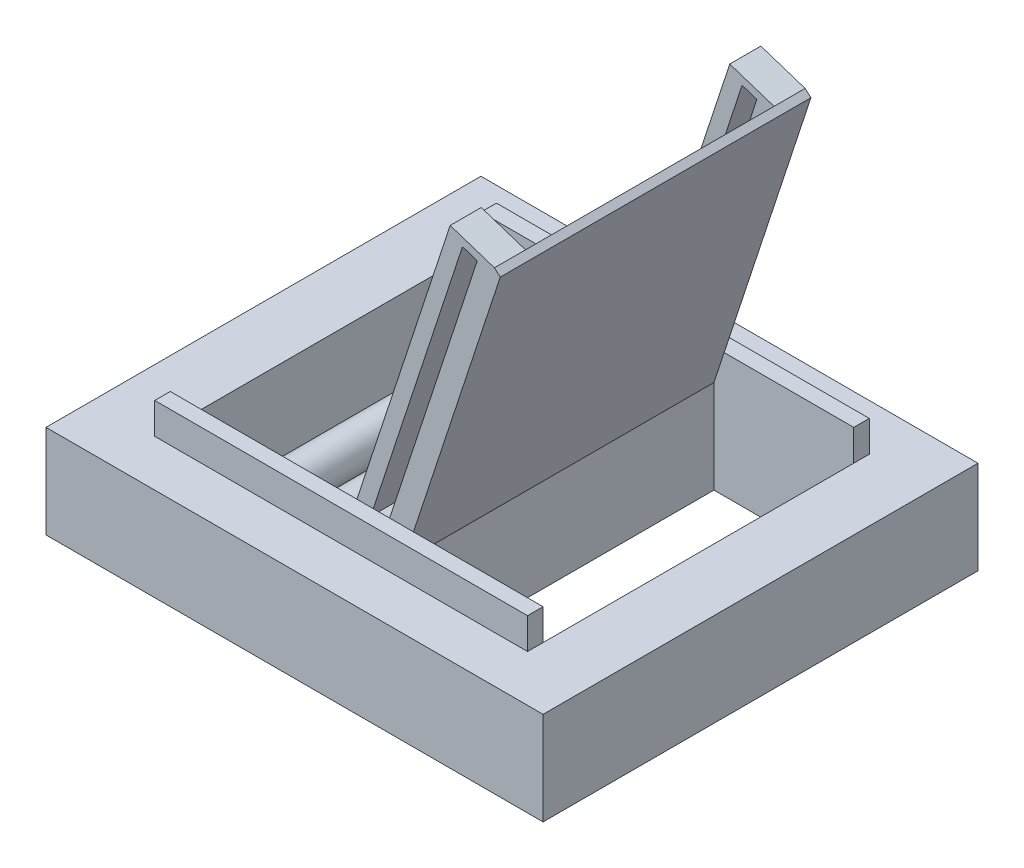
SolidWorks part; units mm, degrees
ref_plane "Front Plane" through (0, 0, 0) normal (0, 0, 1) x (1, 0, 0)
ref_plane "Top Plane" through (0, 0, 0) normal (0, 1, 0) x (1, 0, 0)
ref_plane "Right Plane" through (0, 0, 0) normal (1, 0, 0) x (0, 0, -1)
sketch "Sketch1" plane through (0, 0, 0) normal (0, 1, 0) x (1, 0, 0)
  line L1 (0, 0) -> (812.8, 0)
  line L2 (0, 0) -> (0, -711.2)
  line L3 (0, -711.2) -> (812.8, -711.2)
  line L4 (812.8, 0) -> (812.8, -711.2)
  dimension "D1" = 711.2
  dimension "D2" = 812.8
extrude "Boss-Extrude1" add sketch "Sketch1" along normal blind 152.4
sketch "Sketch2" plane through (0, 152.4, 0) normal (0, 1, 0) x (1, 0, 0)
  line L0 (101.6, -101.6) -> (101.6, -609.6)
  line L5 (101.6, -609.6) -> (711.2, -609.6)
  line L6 (711.2, -101.6) -> (711.2, -609.6)
  line L7 (101.6, -101.6) -> (711.2, -101.6)
extrude "Cut-Extrude1" cut sketch "Sketch2" against normal blind 152.4
sketch "Sketch4" plane through (0, 0, 101.6) normal (0, 0, 1) x (1, 0, 0)
  line L0 (711.2, 0) -> (101.6, 0) construction
  line L1 (101.6, 0) -> (101.6, 152.4) construction
  circle A0 centre (152.4, 25.4) radius 31.75
  dimension "D1" = 63.5
  dimension "D2" = 25.4
  dimension "D3" = 50.8
extrude "Boss-Extrude3" add sketch "Sketch4" along normal up to surface (508 mm away) contours A0 up to face at (406.4, 76.2, 609.6)
sketch "Sketch6" plane through (0, 0, 101.6) normal (0, 0, 1) x (1, 0, 0)
  line L2 (373.3966, 28.575) -> (482.6, 152.4)
  line L4 (711.2, 0) -> (171.45, 0) construction
  line L5 (711.2, 152.4) -> (101.6, 152.4) construction
  line L6 (482.6, 152.4) -> (482.6, 0)
  line L7 (482.6, 0) -> (386.2958, 0)
  arc A0 (386.2958, 0) -> (373.3966, 28.575) centre (348.1958, 0) ccw
  dimension "D1" = 203.2
  dimension "D3" = 76.2
  dimension "D2" = 381
extrude "Boss-Extrude4" add sketch "Sketch6" along normal up to surface (508 mm away) up to face at (321.7333, 60.325, 609.6)
sketch "Sketch7" plane through (0, 0, 101.6) normal (0, 0, 1) x (1, 0, 0)
  circle A0 centre (348.1958, 0) radius 31.75
  dimension "D1" = 63.5
extrude "Boss-Extrude5" add sketch "Sketch7" along normal up to surface (508 mm away) up to face at (250.4811, 55.9876, 609.6)
sketch "Sketch8" plane through (0, 0, 101.6) normal (0, 0, 1) x (1, 0, 0)
  line L0 (373.3966, 28.575) -> (363.8716, 36.9753)
  line L1 (363.8716, 36.9753) -> (473.075, 160.8003)
  line L2 (473.075, 160.8003) -> (482.6, 152.4)
  line L3 (373.3966, 28.575) -> (482.6, 152.4)
  dimension "D1" = 12.7
  dimension "D2" = 165.1
extrude "Boss-Extrude6" add sketch "Sketch8" along normal up to surface (508 mm away) contours L1 L2 L3 L0 up to face at (272.1955, 47.0737, 609.6)
sketch "Sketch9" plane through (0, 0, 609.6) normal (0, 0, 1) x (1, 0, 0)
  line L0 (482.6, 152.4) -> (641.2229, 635)
  line L1 (473.075, 160.8003) -> (631.6979, 643.4003)
  line L2 (631.6979, 643.4003) -> (641.2229, 635)
  line L3 (473.075, 160.8003) -> (482.6, 152.4)
  dimension "D1" = 508
  dimension "D2" = 482.6
  dimension "D3" = 508
extrude "Boss-Extrude7" add sketch "Sketch9" against normal up to surface (508 mm away) up to face at (596.9, 76.2, 101.6)
sketch "Sketch11" plane through (379.2508, -124.6537, 0) normal (-0.95, 0.3122, 0) x (0, 0, 1)
  line L0 (609.6, 300.4779) -> (101.6, 300.4779) construction
  line L1 (609.6, 808.4779) -> (558.8, 808.4779)
  line L2 (609.6, 808.4779) -> (609.6, 300.4779)
  line L3 (609.6, 300.4779) -> (558.8, 300.4779)
  line L4 (558.8, 808.4779) -> (558.8, 300.4779)
  line L6 (101.6, 808.4779) -> (152.4, 808.4779)
  line L7 (101.6, 808.4779) -> (101.6, 300.4779)
  line L8 (101.6, 300.4779) -> (152.4, 300.4779)
  line L9 (152.4, 808.4779) -> (152.4, 300.4779)
  dimension "D1" = 50.8
  dimension "D2" = 50.8
extrude "Boss-Extrude8" add sketch "Sketch11" along normal blind 76.2
sketch "Sketch12" plane through (0, 0, 101.6) normal (0, 0, -1) x (-1, 0, 0)
  line L5 (-579.4724, 647.1976) -> (-429.198, 189.9976)
  line L6 (-453.328, 182.0664) -> (-429.198, 189.9976)
  line L7 (-453.328, 182.0664) -> (-603.6024, 639.2664)
  line L8 (-579.4724, 647.1976) -> (-603.6024, 639.2664)
  line L9 (-559.3079, 667.1937) -> (-400.685, 184.5937) construction
  line L10 (-559.3079, 667.1937) -> (-631.6979, 643.4003) construction
  dimension "D1" = 25.4
  dimension "D2" = 25.4
  dimension "D3" = 457.2
  dimension "D4" = 12.7
extrude "Cut-Extrude2" cut sketch "Sketch12" against normal blind 508
sketch "Sketch14" plane through (0, 152.4, 0) normal (0, 1, 0) x (1, 0, 0)
  line L1 (711.2, -101.6) -> (101.6, -101.6)
  line L2 (711.2, -101.6) -> (711.2, -76.2)
  line L3 (711.2, -76.2) -> (101.6, -76.2)
  line L4 (101.6, -101.6) -> (101.6, -76.2)
  line L5 (101.6, -609.6) -> (711.2, -609.6)
  line L6 (101.6, -609.6) -> (101.6, -635)
  line L7 (101.6, -635) -> (711.2, -635)
  line L8 (711.2, -609.6) -> (711.2, -635)
  dimension "D1" = 609.6
  dimension "D2" = 609.6
  dimension "D3" = 25.4
  dimension "D4" = 25.4
extrude "Boss-Extrude10" add sketch "Sketch14" along normal blind 50.8
sketch "Sketch15" plane through (0, 0, 609.6) normal (0, 0, -1) x (-1, 0, 0)
  line L0 (-406.8006, 203.2) -> (-101.6, 203.2) construction
  line L1 (-101.6, 0) -> (-101.6, 152.4) construction
  circle A0 centre (-342.9, 127) radius 31.75
  dimension "D1" = 63.5
  dimension "D2" = 76.2
  dimension "D3" = 241.3
extrude "Boss-Extrude11" add sketch "Sketch15" along normal blind 508
sketch "Sketch16" plane through (355.1208, -116.7226, 0) normal (-0.95, 0.3122, 0) x (0, 0, 1)
  line L0 (152.4, 808.4779) -> (101.6, 808.4779) construction
  line L1 (609.6, 808.4779) -> (558.8, 808.4779) construction
  line L2 (609.6, 320.0634) -> (609.6, 808.4779) construction
  line L3 (152.4, 300.4779) -> (152.4, 808.4779) construction
  line L4 (152.4, 300.4779) -> (152.4, 808.4779) construction
  line L5 (558.8, 808.4779) -> (558.8, 300.4779) construction
  circle A0 centre (127, 732.2779) radius 63.5
  circle A1 centre (127, 478.2779) radius 50.8
  circle A2 centre (584.2, 732.2779) radius 63.5
  circle A3 centre (584.2, 478.2779) radius 50.8
  dimension "D1" = 127
  dimension "D2" = 127
  dimension "D3" = 101.6
  dimension "D4" = 101.6
  dimension "D5" = 76.2
  dimension "D6" = 76.2
  dimension "D7" = 25.4
  dimension "D8" = 25.4
  dimension "D9" = 25.4
  dimension "D10" = 25.4
  dimension "D11" = 330.2
  dimension "D12" = 330.2
